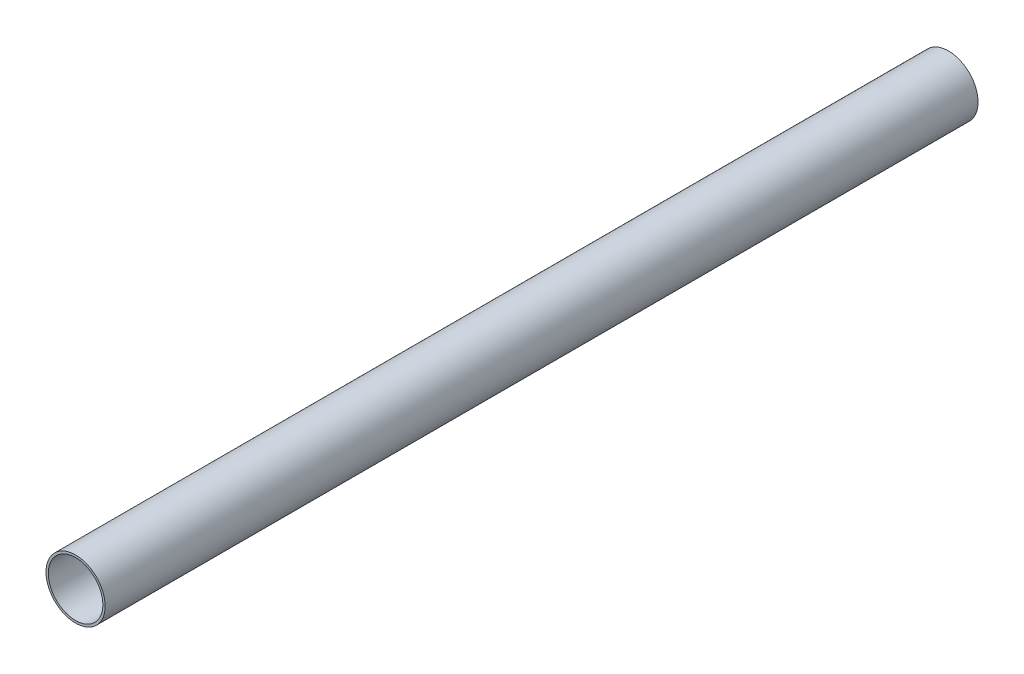
SolidWorks part; units mm, degrees
ref_plane "Front Plane" through (0, 0, 0) normal (0, 0, 1) x (1, 0, 0)
ref_plane "Top Plane" through (0, 0, 0) normal (0, 1, 0) x (1, 0, 0)
ref_plane "Right Plane" through (0, 0, 0) normal (1, 0, 0) x (0, 0, -1)
sketch "Cardboard Motor Tube Sketch" plane through (0, 0, 0) normal (0, 0, 1) x (1, 0, 0)
  circle A0 centre (0, 0) radius 20.6375
  circle A1 centre (0, 0) radius 19.05
  dimension "D1" = 41.275
  dimension "D2" = 38.1
extrude "Boss-Extrude1" add sketch "Cardboard Motor Tube Sketch" along normal blind 609.6
